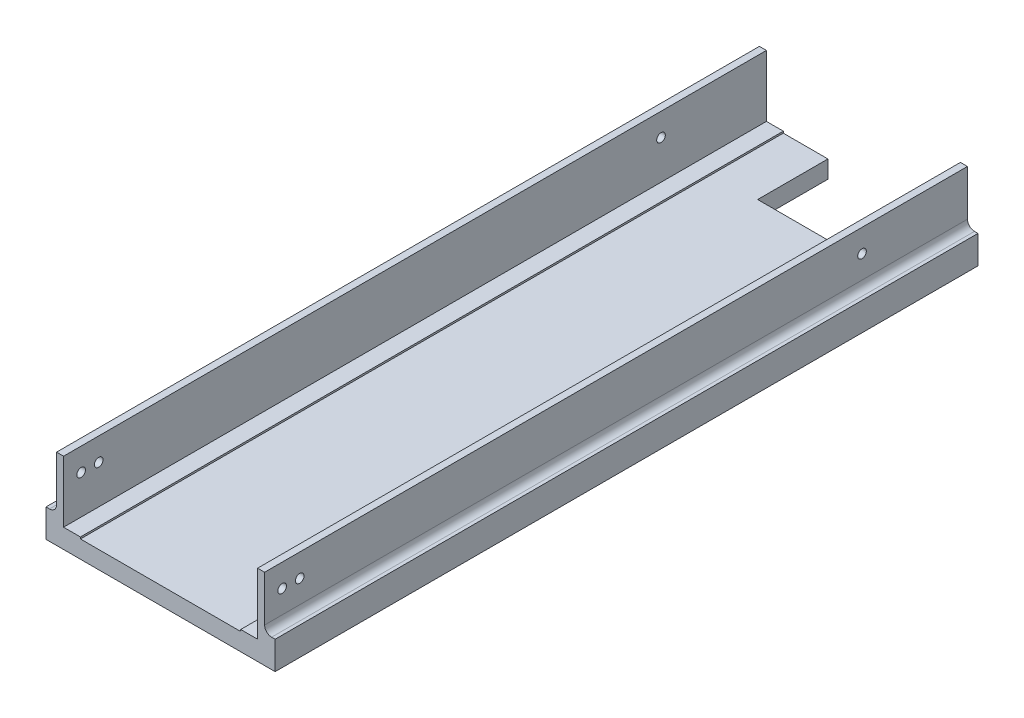
SolidWorks part; units mm, degrees
ref_plane "Front Plane" through (0, 0, 0) normal (0, 0, 1) x (1, 0, 0)
ref_plane "Top Plane" through (0, 0, 0) normal (0, 1, 0) x (1, 0, 0)
ref_plane "Right Plane" through (0, 0, 0) normal (1, 0, 0) x (0, 0, -1)
sketch "Sketch1" plane through (0, 0, 0) normal (0, 0, 1) x (1, 0, 0)
  line L0 (0, 0) -> (0, 25)
  line L1 (0, 25) -> (5, 25)
  line L2 (5, 25) -> (5, 5)
  line L3 (5, 5) -> (60.2, 5)
  line L4 (60.2, 5) -> (60.2, 25)
  line L5 (60.2, 25) -> (65.2, 25)
  line L6 (65.2, 25) -> (65.2, 0)
  line L7 (65.2, 0) -> (0, 0)
  dimension "D1" = 5
  dimension "D2" = 5
  dimension "D3" = 55.2
  dimension "D4" = 5
  dimension "D5" = 20
  dimension "D6" = 20
extrude "Boss-Extrude1" add sketch "Sketch1" along normal blind 400
sketch "Sketch2" plane through (0, 5, 0) normal (0, 1, 0) x (1, 0, 0)
  line L1 (29.51, -63.42) -> (35.69, -63.42)
  line L2 (29.51, -63.42) -> (29.51, -100.67)
  line L3 (29.51, -100.67) -> (35.69, -100.67)
  line L4 (35.69, -63.42) -> (35.69, -100.67)
  line L7 (60.2, -400) -> (5, -400) construction
  line L10 (0, -400) -> (0, 0) construction
  circle A0 centre (32.6, -67.17) radius 2.1
  circle A1 centre (32.6, -96.92) radius 2.1
  circle A2 centre (32.6, -67.17) radius 2.1
  circle A3 centre (32.6, -96.92) radius 2.1
  dimension "D5" = 4.2
  dimension "D1" = 6.18
  dimension "D2" = 37.25
  dimension "D3" = 299.33
  dimension "D4" = 29.51
  dimension "D6" = 3.75
  dimension "D7" = 33.5
  dimension "D8" = 3.09
  dimension "D9" = 3.09
extrude "Cut-Extrude3" cut sketch "Sketch2" against normal blind 10 contours A0 | A1
sketch "Sketch3" plane through (0, 25, 0) normal (0, 1, 0) x (1, 0, 0)
  line L1 (-34.8959, 47.3477) -> (123.1433, 47.3477)
  line L2 (-34.8959, 47.3477) -> (-34.8959, -450.6402)
  line L3 (-34.8959, -450.6402) -> (123.1433, -450.6402)
  line L4 (123.1433, 47.3477) -> (123.1433, -450.6402)
extrude "Cut-Extrude4" cut sketch "Sketch3" against normal blind 2
sketch "Sketch4" plane through (0, 5, 0) normal (0, 1, 0) x (1, 0, 0)
  line L0 (60.2, -400) -> (5, -400) construction
  line L1 (5, 0) -> (9.8, 0)
  line L2 (5, 0) -> (5, -400)
  line L3 (5, -400) -> (9.8, -400)
  line L4 (9.8, 0) -> (9.8, -400)
  line L5 (60.2, 0) -> (5, 0) construction
  line L6 (55.4, 0) -> (60.2, 0)
  line L7 (55.4, 0) -> (55.4, -400)
  line L8 (55.4, -400) -> (60.2, -400)
  line L9 (60.2, 0) -> (60.2, -400)
  dimension "D1" = 4.8
  dimension "D2" = 4.8
extrude "Boss-Extrude2" add sketch "Sketch4" along normal blind 8
sketch "Sketch5" plane through (5, 0, 0) normal (1, 0, 0) x (0, 0, -1)
  line L0 (-400, 13) -> (-400, 23) construction
  line L1 (0, 13) -> (-400, 13) construction
  line L2 (-200, 13) -> (-200, 23)
  line L3 (-400, 23) -> (0, 23) construction
  line L4 (-400, 0) -> (-400, 23) construction
  circle A0 centre (-395, 16.5) radius 1.2
  circle A1 centre (-390, 16.5) radius 1.2
  circle A2 centre (-5, 16.5) radius 1.2
  circle A3 centre (-10, 16.5) radius 1.2
  dimension "D1" = 2.4
  dimension "D2" = 2.4
  dimension "D3" = 5
  dimension "D4" = 10
  dimension "D5" = 3.5
  dimension "D6" = 3.5
  dimension "D7" = 200
extrude "Cut-Extrude9" cut sketch "Sketch5" against normal through all contours A0 | A1 | A3 | A2
sketch "Sketch9" plane through (0, 0, 0) normal (-1, 0, 0) x (0, 0, 1)
  circle A0 centre (5, 16.5) radius 1.225
  circle A1 centre (10, 16.5) radius 1.225
  circle A2 centre (390, 16.5) radius 1.225
  circle A3 centre (395, 16.5) radius 1.225
  dimension "D1" = 2.45
extrude "Cut-Extrude10" cut sketch "Sketch9" against normal through all
sketch "Sketch10" plane through (0, 13, 0) normal (0, 1, 0) x (1, 0, 0)
  line L1 (5, 0) -> (9.8, 0)
  line L2 (5, 0) -> (5, -400)
  line L3 (5, -400) -> (9.8, -400)
  line L4 (9.8, 0) -> (9.8, -400)
  line L5 (55.4, -400) -> (60.2, -400)
  line L6 (55.4, -400) -> (55.4, 0)
  line L7 (55.4, 0) -> (60.2, 0)
  line L8 (60.2, -400) -> (60.2, 0)
extrude "Cut-Extrude11" cut sketch "Sketch10" against normal blind 5
sketch "Sketch12" plane through (0, 0, 0) normal (0, -1, 0) x (1, 0, 0)
  circle A0 centre (32.6, 96.92) radius 2.1
  circle A1 centre (32.6, 67.17) radius 2.1
extrude "Boss-Extrude3" add sketch "Sketch12" against normal blind 15
sketch "Sketch13" plane through (0, 5, 0) normal (0, 1, 0) x (1, 0, 0)
  line L1 (29.51, -63.42) -> (35.69, -63.42)
  line L2 (29.51, -63.42) -> (29.51, -100.67)
  line L3 (29.51, -100.67) -> (35.69, -100.67)
  line L4 (35.69, -63.42) -> (35.69, -100.67)
  circle A0 centre (32.6, -67.17) radius 2.1 construction
  circle A1 centre (32.6, -67.17) radius 2.1 construction
  dimension "D2" = 3.75
  dimension "D1" = 3.09
  dimension "D3" = 37.25
  dimension "D4" = 6.18
extrude "Boss-Extrude5" add sketch "Sketch13" along normal blind 10
sketch "Sketch14" plane through (29.51, 0, 0) normal (-1, 0, 0) x (0, 0, 1)
  line L0 (70.92, 15) -> (75.32, 19.4)
  line L1 (63.42, 15) -> (100.67, 15) construction
  line L2 (75.32, 19.4) -> (88.77, 19.4)
  line L3 (88.77, 19.4) -> (93.17, 15)
  line L4 (63.42, 15) -> (63.42, 5) construction
  line L5 (70.92, 15) -> (93.17, 15)
  dimension "D1" = 13.45
  dimension "D2" = 4.4
  dimension "D3" = 4.4
  dimension "D4" = 4.4
  dimension "D5" = 7.5
extrude "Boss-Extrude6" add sketch "Sketch14" against normal up to surface (6.18 mm away) up to face at (35.69, 10, 82.045)
sketch "Sketch15" plane through (29.51, 0, 0) normal (-1, 0, 0) x (0, 0, 1)
  line L0 (100.67, 15) -> (100.67, 5) construction
  line L1 (63.42, 15) -> (63.42, 5) construction
  line L2 (88.77, 19.4) -> (75.32, 19.4) construction
  circle A0 centre (78.87, 16) radius 1.05
  circle A1 centre (85.22, 16) radius 1.05
  dimension "D4" = 3.4
  dimension "D5" = 2.1
  dimension "D6" = 2.1
  dimension "D1" = 15.45
  dimension "D2" = 15.45
  dimension "D3" = 3.4
extrude "Cut-Extrude12" cut sketch "Sketch15" against normal blind 10
fillet "Fillet1" radius 2 8 edges at (29.51, 10, 100.67) (35.69, 10, 100.67) (35.69, 10, 63.42) (29.51, 10, 63.42) (32.6, 5, 100.67) (35.69, 5, 82.045) (32.6, 5, 63.42) (29.51, 5, 82.045)
sketch "Sketch16" plane through (0, 8, 0) normal (0, 1, 0) x (1, 0, 0)
  line L1 (5, 0) -> (9.8, 0)
  line L2 (5, 0) -> (5, -400)
  line L3 (5, -400) -> (9.8, -400)
  line L4 (9.8, 0) -> (9.8, -400)
  line L5 (55.4, -400) -> (60.2, -400)
  line L6 (55.4, -400) -> (55.4, 0)
  line L7 (55.4, 0) -> (60.2, 0)
  line L8 (60.2, -400) -> (60.2, 0)
extrude "Cut-Extrude13" cut sketch "Sketch16" against normal blind 2.5
sketch "Sketch17" plane through (29.51, 0, 0) normal (-1, 0, 0) x (0, 0, 1)
  circle A0 centre (78.87, 16) radius 1.16
  circle A1 centre (85.22, 16) radius 1.16
  dimension "D1" = 2.32
  dimension "D2" = 2.32
extrude "Cut-Extrude14" cut sketch "Sketch17" against normal up to next
sketch "Sketch18" plane through (60.2, 0, 0) normal (-1, 0, 0) x (0, 0, 1)
  line L0 (5, 16.5) -> (170, 16.5)
  circle A0 centre (170, 16.5) radius 1.225
  circle A1 centre (5, 16.5) radius 1.225 construction
  dimension "D1" = 165
extrude "Cut-Extrude16" cut sketch "Sketch18" against normal through all and the other way through all
sketch "Sketch20" plane through (60.2, 0, 0) normal (-1, 0, 0) x (0, 0, 1)
  line L0 (395, 16.5) -> (230, 16.5)
  circle A0 centre (230, 16.5) radius 1.225
  circle A1 centre (395, 16.5) radius 1.225 construction
  dimension "D1" = 165
extrude "Cut-Extrude17" cut sketch "Sketch20" against normal through all and the other way through all
sketch "Sketch22" plane through (0, 0, 0) normal (0, 0, -1) x (-1, 0, 0)
  line L1 (-65.2, 23) -> (-62.2, 23)
  line L2 (-65.2, 23) -> (-65.2, 8)
  line L3 (-65.2, 8) -> (-62.2, 8)
  line L4 (-62.2, 23) -> (-62.2, 8)
  line L5 (0, 23) -> (-3, 23)
  line L6 (0, 23) -> (0, 8)
  line L7 (0, 8) -> (-3, 8)
  line L8 (-3, 23) -> (-3, 8)
  dimension "D1" = 15
  dimension "D2" = 3
  dimension "D3" = 3
  dimension "D4" = 15
extrude "Cut-Extrude18" cut sketch "Sketch22" against normal through all
fillet "Fillet2" radius 2 1 edges at (62.2, 8, 200)
fillet "Fillet3" radius 2 1 edges at (3, 8, 200)
sketch "Sketch24" plane through (0, 23, 0) normal (0, 1, 0) x (1, 0, 0)
  line L0 (0, -200) -> (65.2, -200)
  line L1 (0, 0) -> (65.2, 0)
  line L2 (0, 0) -> (0, -400)
  line L3 (0, -400) -> (65.2, -400)
  line L4 (65.2, 0) -> (65.2, -400)
  line L6 (22.5, -200) -> (42.7, -200)
  line L7 (22.5, -200) -> (22.5, -220)
  line L8 (22.5, -220) -> (42.7, -220)
  line L9 (42.7, -200) -> (42.7, -220)
  line M3 (62.2, -400) -> (62.2, 0)
  line M4 (62.2, 0) -> (60.2, 0)
  line M5 (60.2, 0) -> (60.2, -400)
  dimension "D1" = 20.2
  dimension "D2" = 22.5
  dimension "D3" = 20
extrude "Cut-Extrude21" cut sketch "Sketch24" against normal through all contours L1 L2 L0 M5 | L9 L0 L7 L8 | L0 M5 M3 M4 | L4 L1 L0 M3
